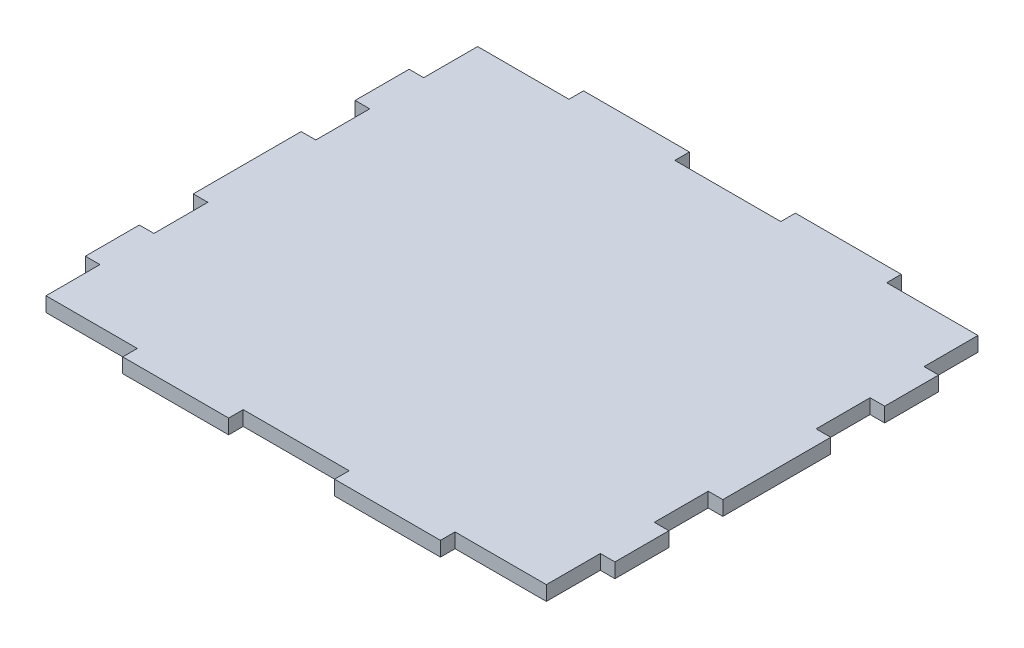
SolidWorks part; units mm, degrees
ref_plane "Front Plane" through (0, 0, 0) normal (0, 0, 1) x (1, 0, 0)
ref_plane "Top Plane" through (0, 0, 0) normal (0, 1, 0) x (1, 0, 0)
ref_plane "Right Plane" through (0, 0, 0) normal (1, 0, 0) x (0, 0, -1)
sketch "Sketch1" plane through (0, 0, 0) normal (0, 1, 0) x (1, 0, 0)
  line L1 (-199.2391, 36.9171) -> (154.7657, 36.9171)
  line L2 (-199.2391, 36.9171) -> (-199.2391, -271.1341)
  line L3 (-199.2391, -271.1341) -> (154.7657, -271.1341)
  line L4 (154.7657, 36.9171) -> (154.7657, -271.1341)
  dimension "D1" = 354.0049
  dimension "D2" = 308.0512
extrude "Boss-Extrude1" add sketch "Sketch1" along normal blind 9.7536
sketch "Sketch2" plane through (0, 9.7536, 0) normal (0, 1, 0) x (1, 0, 0)
  line L0 (-22.2367, 36.9171) -> (-22.2367, -271.1341) construction
  line L1 (154.7657, 36.9171) -> (-199.2391, 36.9171) construction
  line L2 (-199.2391, -271.1341) -> (154.7657, -271.1341) construction
  line L3 (-199.2391, -117.1085) -> (154.7657, -117.1085) construction
  line L4 (-199.2391, 36.9171) -> (-199.2391, -271.1341) construction
  line L5 (154.7657, -271.1341) -> (154.7657, 36.9171) construction
  line L6 (13.1638, 27.1635) -> (-57.6372, 27.1635)
  line L7 (13.1638, -271.1341) -> (-57.6372, -271.1341)
  line L8 (-22.2367, -271.1341) -> (-22.2367, -261.3805)
  line L9 (13.1638, -261.3805) -> (-57.6372, -261.3805)
  line L10 (-57.6372, -271.1341) -> (-57.6372, -261.3805)
  line L11 (-57.6372, -271.1341) -> (-128.4382, -271.1341)
  line L12 (-57.6372, -271.1341) -> (-57.6372, -261.3805)
  line L14 (-128.4382, -271.1341) -> (-128.4382, -261.3805)
  line L15 (-128.4382, -271.1341) -> (-199.2391, -271.1341)
  line L16 (-128.4382, -271.1341) -> (-128.4382, -261.3805)
  line L17 (-128.4382, -261.3805) -> (-199.2391, -261.3805)
  line L18 (-199.2391, -271.1341) -> (-199.2391, -261.3805)
  line L19 (-199.2391, -261.3805) -> (-189.4855, -261.3805)
  line L20 (-199.2391, -261.3805) -> (-199.2391, -225.3125)
  line L21 (-199.2391, -225.3125) -> (-189.4855, -225.3125)
  line L22 (-189.4855, -261.3805) -> (-189.4855, -225.3125)
  line L23 (-199.2391, -153.1765) -> (-189.4855, -153.1765)
  line L24 (-199.2391, -153.1765) -> (-199.2391, -189.2445)
  line L25 (-199.2391, -189.2445) -> (-189.4855, -189.2445)
  line L26 (-189.4855, -153.1765) -> (-189.4855, -189.2445)
  line L27 (-57.6372, 36.9171) -> (-57.6372, 27.1635)
  line L28 (13.1638, 36.9171) -> (-57.6372, 36.9171)
  line L29 (-22.2367, 36.9171) -> (-22.2367, 27.1635)
  line L30 (-128.4382, 27.1635) -> (-199.2391, 27.1635)
  line L31 (-199.2391, 36.9171) -> (-199.2391, 27.1635)
  line L32 (-128.4382, 36.9171) -> (-199.2391, 36.9171)
  line L33 (-128.4382, 36.9171) -> (-128.4382, 27.1635)
  line L34 (-199.2391, -8.9045) -> (-189.4855, -8.9045)
  line L35 (-189.4855, 27.1635) -> (-189.4855, -8.9045)
  line L36 (-199.2391, 27.1635) -> (-189.4855, 27.1635)
  line L37 (-199.2391, 27.1635) -> (-199.2391, -8.9045)
  line L38 (-199.2391, -44.9725) -> (-189.4855, -44.9725)
  line L39 (-189.4855, -81.0405) -> (-189.4855, -44.9725)
  line L40 (-199.2391, -81.0405) -> (-189.4855, -81.0405)
  line L41 (-199.2391, -81.0405) -> (-199.2391, -44.9725)
  line L42 (13.1638, -271.1341) -> (13.1638, -261.3805)
  line L43 (83.9648, -261.3805) -> (154.7657, -261.3805)
  line L44 (154.7657, -271.1341) -> (154.7657, -261.3805)
  line L45 (83.9648, -271.1341) -> (154.7657, -271.1341)
  line L46 (83.9648, -271.1341) -> (83.9648, -261.3805)
  line L47 (154.7657, -225.3125) -> (145.0121, -225.3125)
  line L48 (145.0121, -261.3805) -> (145.0121, -225.3125)
  line L49 (154.7657, -261.3805) -> (145.0121, -261.3805)
  line L50 (154.7657, -261.3805) -> (154.7657, -225.3125)
  line L51 (154.7657, -189.2445) -> (145.0121, -189.2445)
  line L52 (145.0121, -153.1765) -> (145.0121, -189.2445)
  line L53 (154.7657, -153.1765) -> (145.0121, -153.1765)
  line L54 (154.7657, -153.1765) -> (154.7657, -189.2445)
  line L55 (154.7657, -81.0405) -> (154.7657, -44.9725)
  line L56 (154.7657, -81.0405) -> (145.0121, -81.0405)
  line L57 (145.0121, -81.0405) -> (145.0121, -44.9725)
  line L58 (154.7657, -44.9725) -> (145.0121, -44.9725)
  line L59 (154.7657, 27.1635) -> (145.0121, 27.1635)
  line L60 (145.0121, 27.1635) -> (145.0121, -8.9045)
  line L61 (154.7657, -8.9045) -> (145.0121, -8.9045)
  line L62 (154.7657, 27.1635) -> (154.7657, -8.9045)
  line L63 (83.9648, 27.1635) -> (154.7657, 27.1635)
  line L64 (83.9648, 36.9171) -> (83.9648, 27.1635)
  line L65 (83.9648, 36.9171) -> (154.7657, 36.9171)
  line L66 (154.7657, 36.9171) -> (154.7657, 27.1635)
  line L67 (13.1638, 36.9171) -> (13.1638, 27.1635)
  point P26 (-22.2367, -117.1085)
  line M1 (-199.2391, 36.9171) -> (-199.2391, -271.1341)
  line M2 (-199.2391, -271.1341) -> (154.7657, -271.1341)
  dimension "D1" = 9.7536
  dimension "D2" = 9.7536
  dimension "D3" = 70.801
  dimension "D4" = 35.4005
  dimension "D5" = 70.801
  dimension "D6" = 9.7536
  dimension "D7" = 9.7536
  dimension "D8" = 36.068
  dimension "D9" = 36.068
  dimension "D10" = 36.068
  dimension "D11" = 36.068
extrude "Cut-Extrude1" cut sketch "Sketch2" against normal through all contours L26 L23 L25 M1 | L17 L22 L21 M1 | L14 L17 M1 M2 | L7 L42 L9 L8 | L10 L8 L9 M2 | L44 L45 L46 L43 | L50 L47 L48 L49 | L51 L52 L53 L54 | L55 L58 L57 L56 | L59 L60 L61 L62 | L66 L65 L64 L63 | L28 L27 L6 L67 | L38 L39 L40 L41 | L37 L34 L35 L36 | L31 L32 L33 L30
equation "\"D1@Sketch1\"=\"Base Length@Assembled Container.Assembly\""
equation "\"D2@Sketch1\"=\"Base Width@Assembled Container.Assembly\""
equation "\"D1@Boss-Extrude1\"=\"Acrylic Thickness@Assembled Container.Assembly\""
equation "\"D1@Sketch2\"=\"Acrylic Thickness@Assembled Container.Assembly\""
equation "\"D2@Sketch2\"=\"Acrylic Thickness@Assembled Container.Assembly\""
equation "\"D4@Sketch2\"=\"Lid Long Side Inner Cutout@Assembled Container.Assembly\""
equation "\"D3@Sketch2\"=\"Lid Long Side Outer Cutout@Assembled Container.Assembly\""
equation "\"D6@Sketch2\"=\"Acrylic Thickness@Assembled Container.Assembly\""
equation "\"D7@Sketch2\"=\"Acrylic Thickness@Assembled Container.Assembly\""
equation "\"D8@Sketch2\"=\"Lid Short Side Outer Cutout@Assembled Container.Assembly\""
equation "\"D9@Sketch2\"=\"Lid Short Side Outer Overhang@Assembled Container.Assembly\""
equation "\"D10@Sketch2\"=\"Lid Short Side Middle Cutout@Assembled Container.Assembly\""
